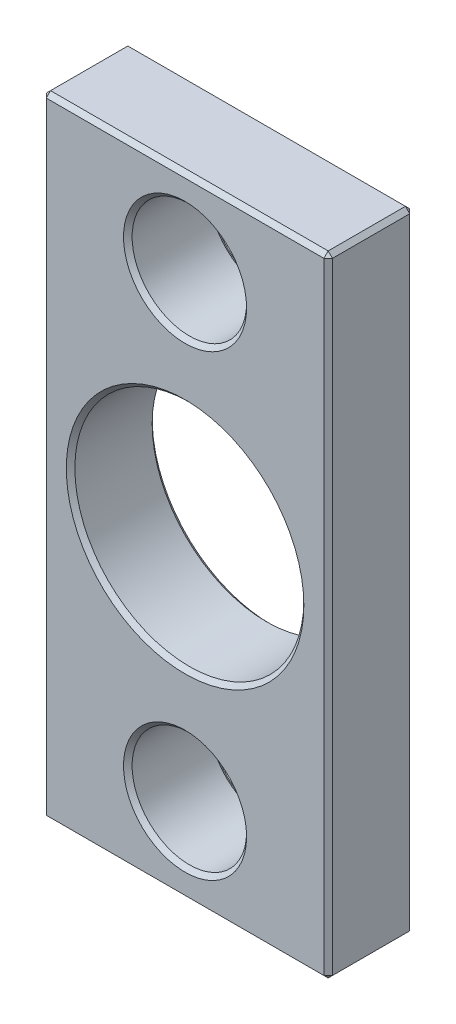
SolidWorks part; units mm, degrees
ref_plane "Front Plane" through (0, 0, 0) normal (0, 0, 1) x (1, 0, 0)
ref_plane "Top Plane" through (0, 0, 0) normal (0, 1, 0) x (1, 0, 0)
ref_plane "Right Plane" through (0, 0, 0) normal (1, 0, 0) x (0, 0, -1)
sketch "Sketch1" plane through (0, 0, 0) normal (0, 0, 1) x (1, 0, 0)
  line L1 (-5, 11) -> (5, 11)
  line L2 (-5, 11) -> (-5, -11)
  line L3 (-5, -11) -> (5, -11)
  line L4 (5, 11) -> (5, -11)
  circle A0 centre (0, 0) radius 4
  circle A1 centre (0, -8) radius 2
  circle A2 centre (0, 8) radius 2
  point P4 (0, 11)
  point P6 (-5, 0)
  point P13 (0, 0)
  point P15 (-0.1384, 11)
  dimension "D3" = 4
  dimension "D4" = 8
  dimension "D5" = 4
  dimension "D1" = 5
  dimension "D2" = 11
  dimension "D6" = 3
  dimension "D7" = 8
  dimension "D9" = 3
extrude "Boss-Extrude1" add sketch "Sketch1" along normal mid plane 3
chamfer "Chamfer1" distance 0.15 angle 45 18 edges at (2, 8, -1.5) (2, -8, -1.5) (4, 0, -1.5) (2, 8, 1.5) (4, 0, 1.5) (-5, -11, 0) (0, -11, -1.5) (-5, 0, -1.5) (5, -11, 0) (5, 0, -1.5) (5, 11, 0) (0, 11, -1.5) (-5, 11, 0) (0, 11, 1.5) (5, 0, 1.5) (0, -11, 1.5) (-5, 0, 1.5) (2, -8, 1.5)
